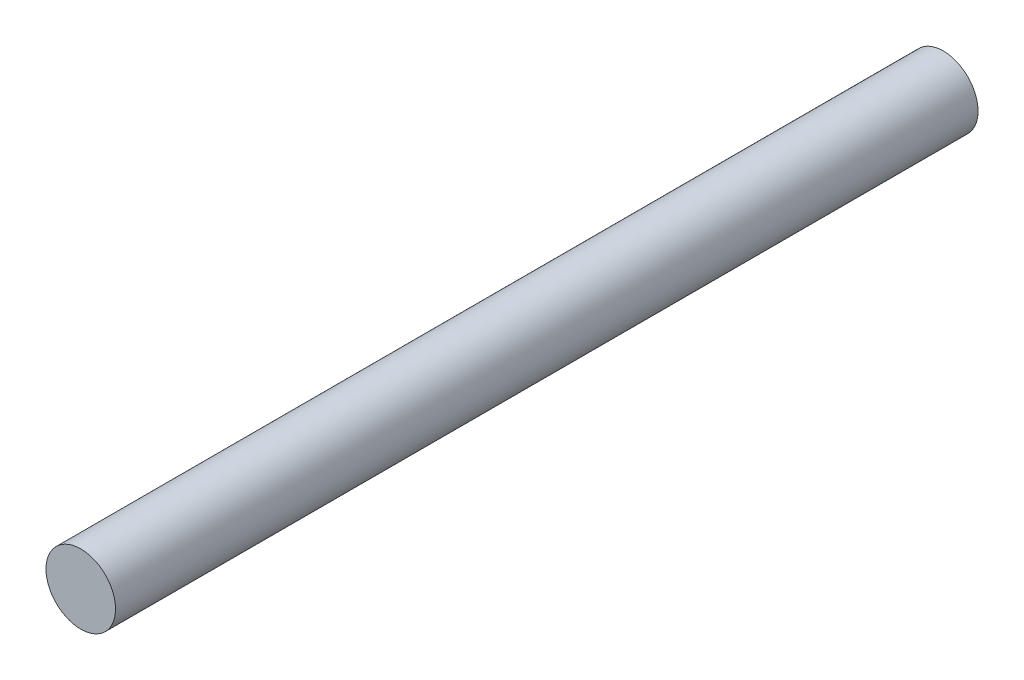
SolidWorks part; units mm, degrees
ref_plane "Front Plane" through (0, 0, 0) normal (0, 0, 1) x (1, 0, 0)
ref_plane "Top Plane" through (0, 0, 0) normal (0, 1, 0) x (1, 0, 0)
ref_plane "Right Plane" through (0, 0, 0) normal (1, 0, 0) x (0, 0, -1)
sketch "Sketch1" plane through (0, 0, 0) normal (0, 0, 1) x (1, 0, 0)
  circle A0 centre (0, 0) radius 1
  dimension "D1" = 2
extrude "Boss-Extrude1" add sketch "Sketch1" along normal blind 24.8
